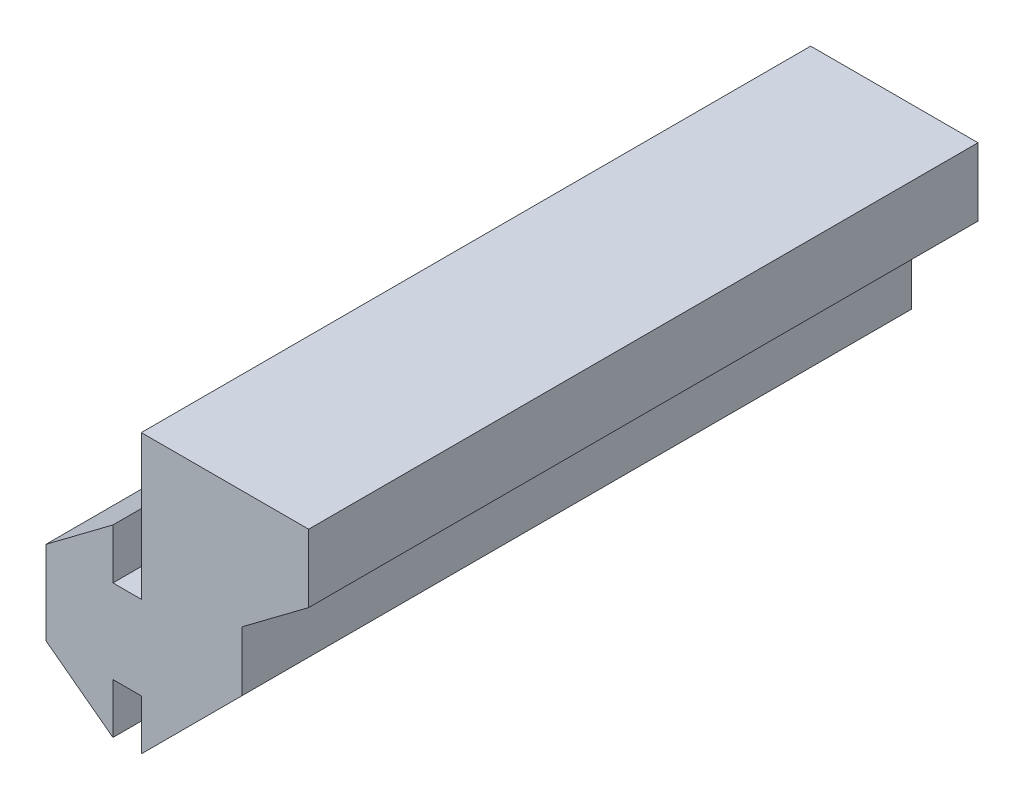
SolidWorks part; units mm, degrees
ref_plane "Plan de face" through (0, 0, 0) normal (0, 0, 1) x (1, 0, 0)
ref_plane "Plan de dessus" through (0, 0, 0) normal (0, 1, 0) x (1, 0, 0)
ref_plane "Plan de droite" through (0, 0, 0) normal (1, 0, 0) x (0, 0, -1)
sketch "Main - Sketch" plane through (0, 0, 0) normal (0, 0, 1) x (1, 0, 0)
  line L0 (0, 0) -> (0, 5)
  line L1 (0, 5) -> (4, 8)
  line L2 (0, 0) -> (4, -3)
  line L3 (4, 8) -> (4, 5)
  line L4 (4, 5) -> (5.6958, 5)
  line L5 (5.6958, 0) -> (5.6958, -3)
  line L6 (5.6958, 0) -> (4, 0)
  line L7 (4, 0) -> (4, -3)
  line L8 (15.6958, 13.6284) -> (5.6958, 13.6284)
  line L9 (5.6958, 13.6284) -> (5.6958, 5)
  line L10 (5.6958, -3) -> (11.7102, 3.0144)
  line L11 (11.7102, 3.0144) -> (11.7102, 6.5819)
  line L12 (11.7102, 6.5819) -> (15.6958, 9.5711)
  line L13 (15.6958, 9.5711) -> (15.6958, 13.6284)
  dimension "D1" = 4
  dimension "D2" = 5.6958
  dimension "D3" = 5
  dimension "D4" = 8
  dimension "D5" = 45
  dimension "D6" = 10
  dimension "D7" = 11
extrude "Main - Extrusion" add sketch "Main - Sketch" along normal blind 40
